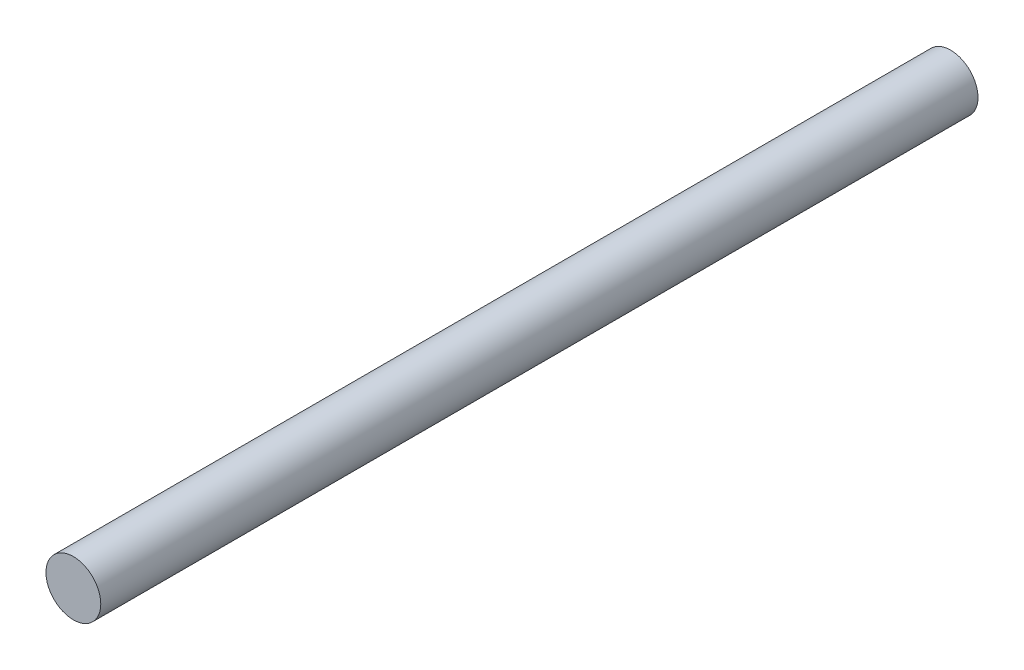
SolidWorks part; units mm, degrees
ref_plane "Спереди" through (0, 0, 0) normal (0, 0, 1) x (1, 0, 0)
ref_plane "Сверху" through (0, 0, 0) normal (0, 1, 0) x (1, 0, 0)
ref_plane "Справа" through (0, 0, 0) normal (1, 0, 0) x (0, 0, -1)
sketch "Эскиз1" plane through (0, 0, 0) normal (0, 0, 1) x (1, 0, 0)
  circle A0 centre (0, 0) radius 2.5
  dimension "D1" = 5
extrude "Вытянуть1" add sketch "Эскиз1" along normal blind 80
